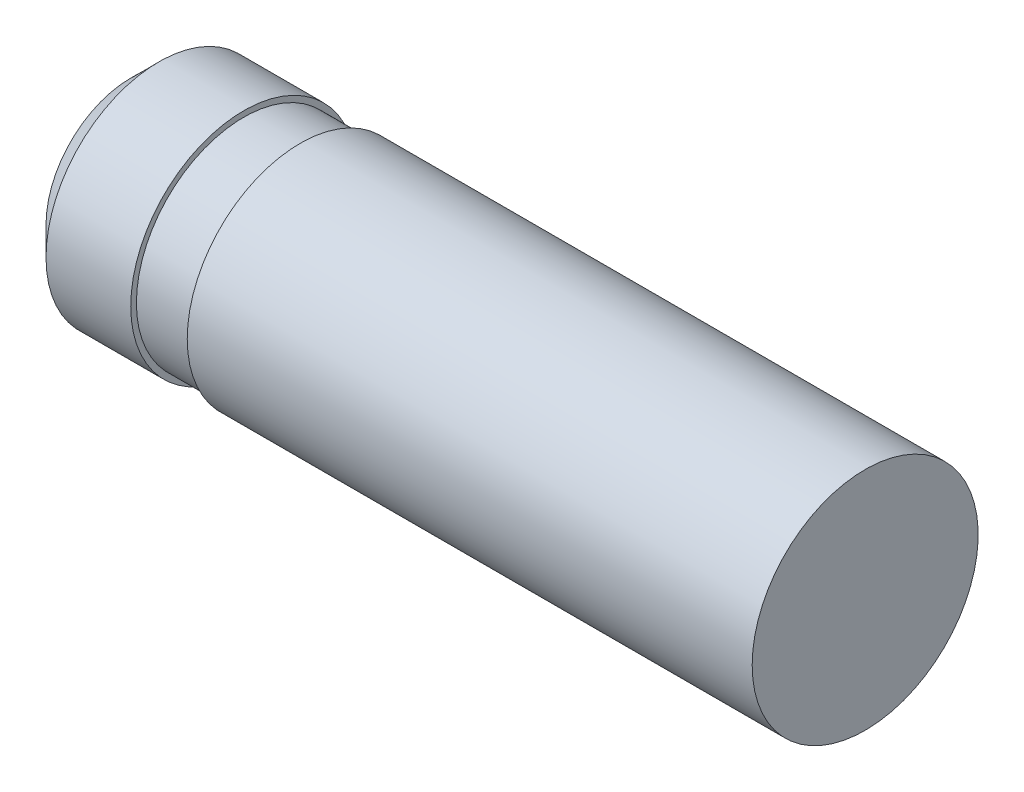
SolidWorks part; units mm, degrees
ref_plane "Front Plane" through (0, 0, 0) normal (0, 0, 1) x (1, 0, 0)
ref_plane "Top Plane" through (0, 0, 0) normal (0, 1, 0) x (1, 0, 0)
ref_plane "Right Plane" through (0, 0, 0) normal (1, 0, 0) x (0, 0, -1)
sketch "Sketch1" plane through (0, 0, 0) normal (0, 0, 1) x (1, 0, 0)
  line L0 (-11.4441, 0) -> (11.3059, 0) construction
  line L1 (4.5638, -2) -> (-5.4362, -2)
  line L2 (-5.4362, -2) -> (-5.4362, -1.9)
  line L3 (-5.4362, -1.9) -> (-6.4362, -1.9)
  line L4 (-6.4362, -1.9) -> (-6.4362, -2)
  line L5 (-6.4362, -2) -> (-8.4362, -2)
  line L6 (-8.4362, -2) -> (-8.4362, 0)
  line L7 (4.5638, -2) -> (4.5638, 0)
  line L8 (4.5638, 0) -> (-8.4362, 0)
  dimension "D1" = 13
  dimension "D2" = 10
  dimension "D3" = 2
  dimension "D4" = 2
  dimension "D5" = 2
  dimension "D6" = 1.9
revolve "Revolve1" add sketch "Sketch1" angle 360 about L0
chamfer "Chamfer1" distance 0.5 angle 45 1 edges at (-8.4362, 0, 2)
